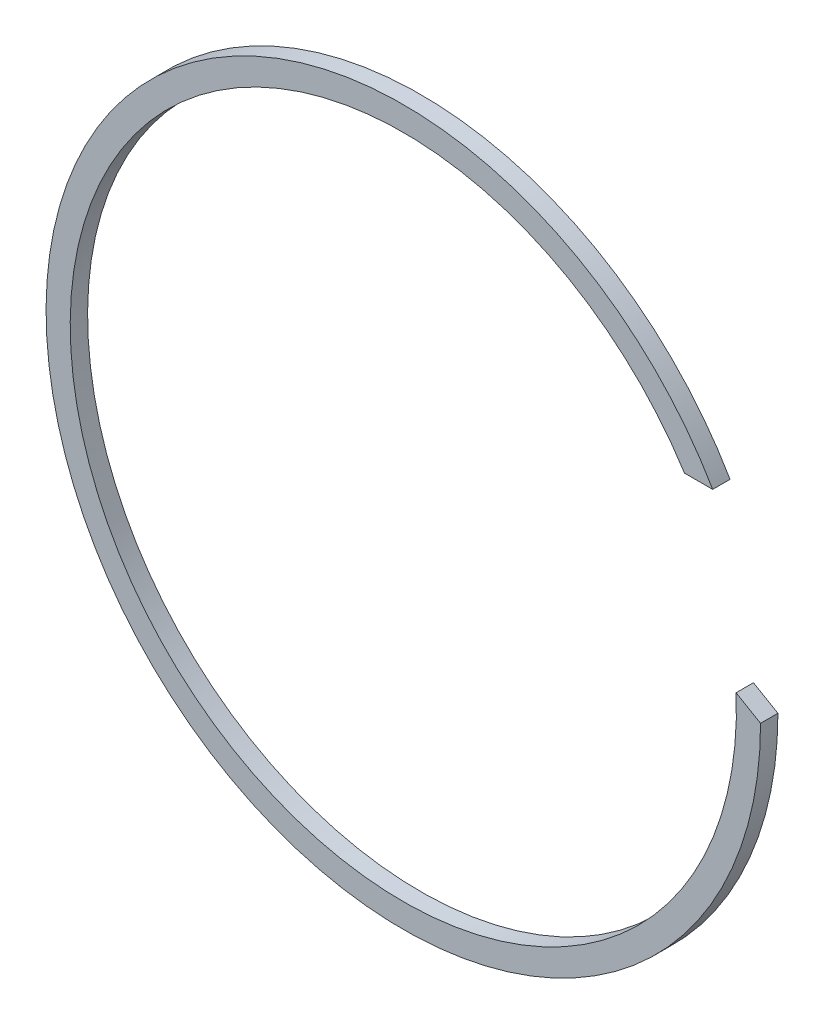
SolidWorks part; units mm, degrees
ref_plane "Plan1" through (0, 0, 0) normal (0, 0, 1) x (1, 0, 0)
ref_plane "Plan2" through (0, 0, 0) normal (0, 1, 0) x (1, 0, 0)
ref_plane "Plan3" through (0, 0, 0) normal (1, 0, 0) x (0, 0, -1)
sketch "Esquisse1" plane through (0, 0, 0) normal (0, 0, 1) x (1, 0, 0)
  line L0 (0, 0) -> (60, 0) construction
  line L1 (0, 0) -> (-33.541, 58.0948) construction
  line L2 (37, 0) -> (34.4684, 1.4752)
  line L3 (0, 0) -> (54.1136, 31.2425) construction
  line L5 (32.0429, 18.5) -> (29.1204, 18.5)
  arc A0 (32.0429, 18.5) -> (37, 0) centre (0, 0) ccw
  arc A1 (29.1204, 18.5) -> (34.4684, 1.4752) centre (0, 0) ccw
  dimension "D1" = 74
  dimension "D2" = 69
  dimension "D3" = 120
  dimension "D4" = 30
extrude "Base-Extrusion" add sketch "Esquisse1" along normal blind 1.8
